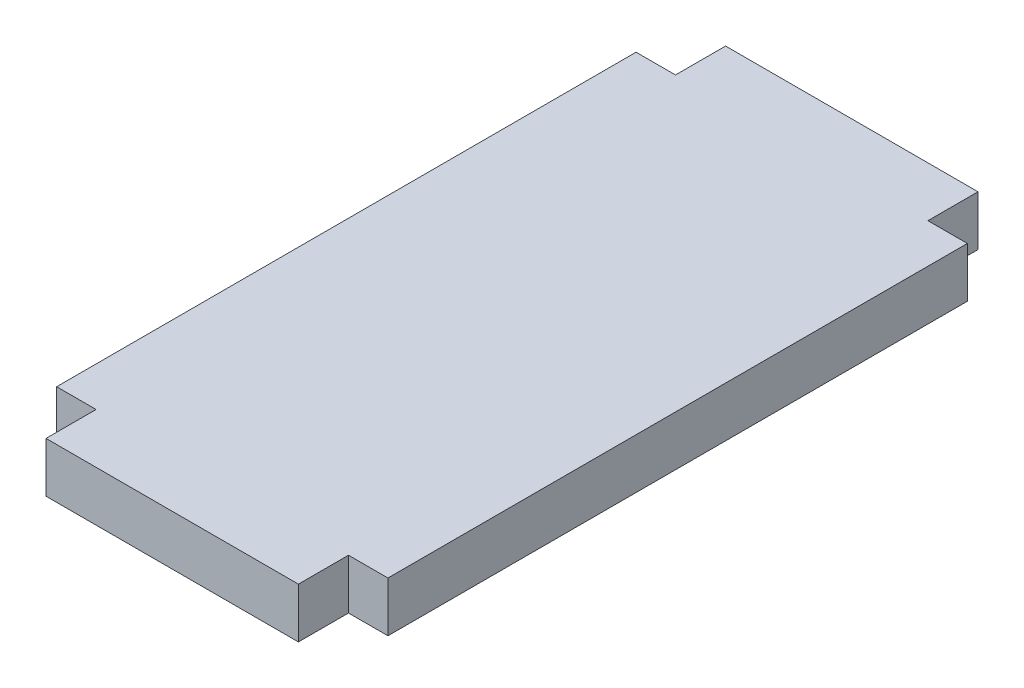
SolidWorks part; units mm, degrees
ref_plane "Front Plane" through (0, 0, 0) normal (0, 0, 1) x (1, 0, 0)
ref_plane "Top Plane" through (0, 0, 0) normal (0, 1, 0) x (1, 0, 0)
ref_plane "Right Plane" through (0, 0, 0) normal (1, 0, 0) x (0, 0, -1)
sketch "Sketch1" plane through (0, 0, 0) normal (0, 1, 0) x (1, 0, 0)
  line L1 (-10.5, 18.365) -> (10.5, 18.365)
  line L2 (-10.5, 18.365) -> (-10.5, -18.365)
  line L3 (-10.5, -18.365) -> (10.5, -18.365)
  line L4 (10.5, 18.365) -> (10.5, -18.365)
  line L5 (-10.5, 18.365) -> (10.5, -18.365) construction
  line L6 (-10.5, -18.365) -> (10.5, 18.365) construction
  line L7 (-8, 21.54) -> (8, 21.54)
  line L8 (-8, 21.54) -> (-8, -21.54)
  line L9 (-8, -21.54) -> (8, -21.54)
  line L10 (8, 21.54) -> (8, -21.54)
  line L11 (-8, 21.54) -> (8, -21.54) construction
  line L12 (-8, -21.54) -> (8, 21.54) construction
  point P0 (0, 0)
  point P6 (0, 0)
  dimension "D1" = 21
  dimension "D2" = 16
  dimension "D3" = 3.175
  dimension "D4" = 3.175
  dimension "D5" = 36.73
extrude "Boss-Extrude1" add sketch "Sketch1" along normal blind 3.175 contours L8 L1 L2 L3 | L10 L1 L8 L3 | L1 L10 L3 L4 | L10 L3 L8 L9 | L10 L7 L8 L1
